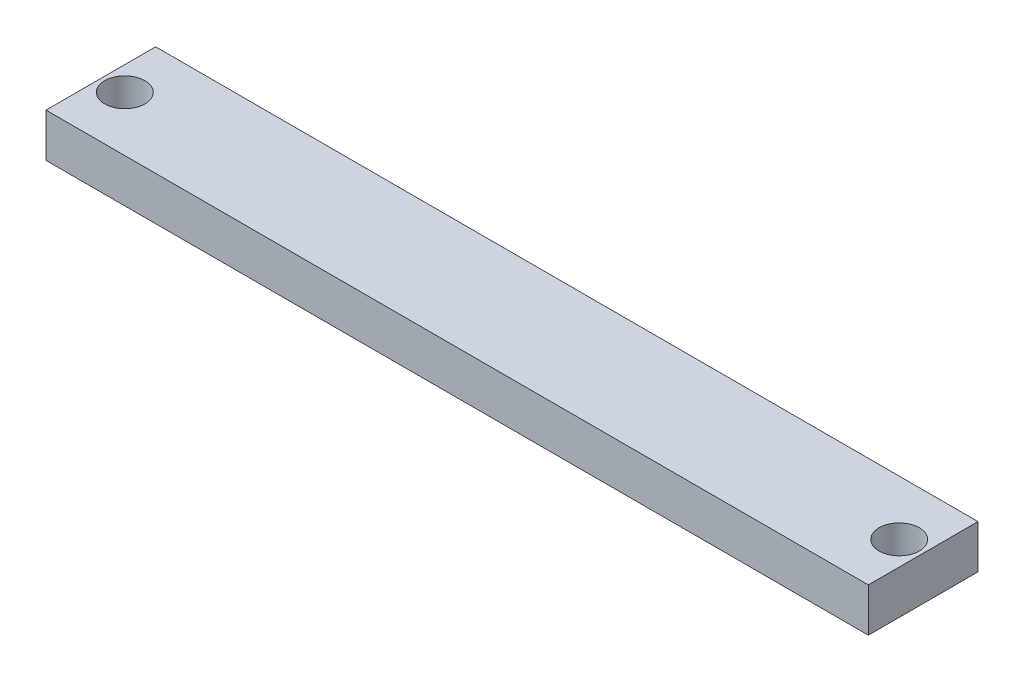
SolidWorks part; units mm, degrees
ref_plane "Front Plane" through (0, 0, 0) normal (0, 0, 1) x (1, 0, 0)
ref_plane "Top Plane" through (0, 0, 0) normal (0, 1, 0) x (1, 0, 0)
ref_plane "Right Plane" through (0, 0, 0) normal (1, 0, 0) x (0, 0, -1)
sketch "Sketch1" plane through (0, 0, 0) normal (0, 1, 0) x (1, 0, 0)
  line L0 (-30, 0) -> (30, 0) construction
  line L1 (-30, 4) -> (30, 4)
  line L2 (-30, 4) -> (-30, -4)
  line L3 (-30, -4) -> (30, -4)
  line L4 (30, 4) -> (30, -4)
  line L5 (-30, 4) -> (30, -4) construction
  line L6 (-30, -4) -> (30, 4) construction
  line L7 (0, 4) -> (0, -4) construction
  circle A0 centre (-28.25, 0) radius 1.47
  circle A1 centre (28.25, 0) radius 1.47
  point P0 (0, 0)
  dimension "D3" = 1.75
  dimension "D4" = 2.94
  dimension "D1" = 8
  dimension "D2" = 60
extrude "Boss-Extrude1" add sketch "Sketch1" along normal blind 3.18
